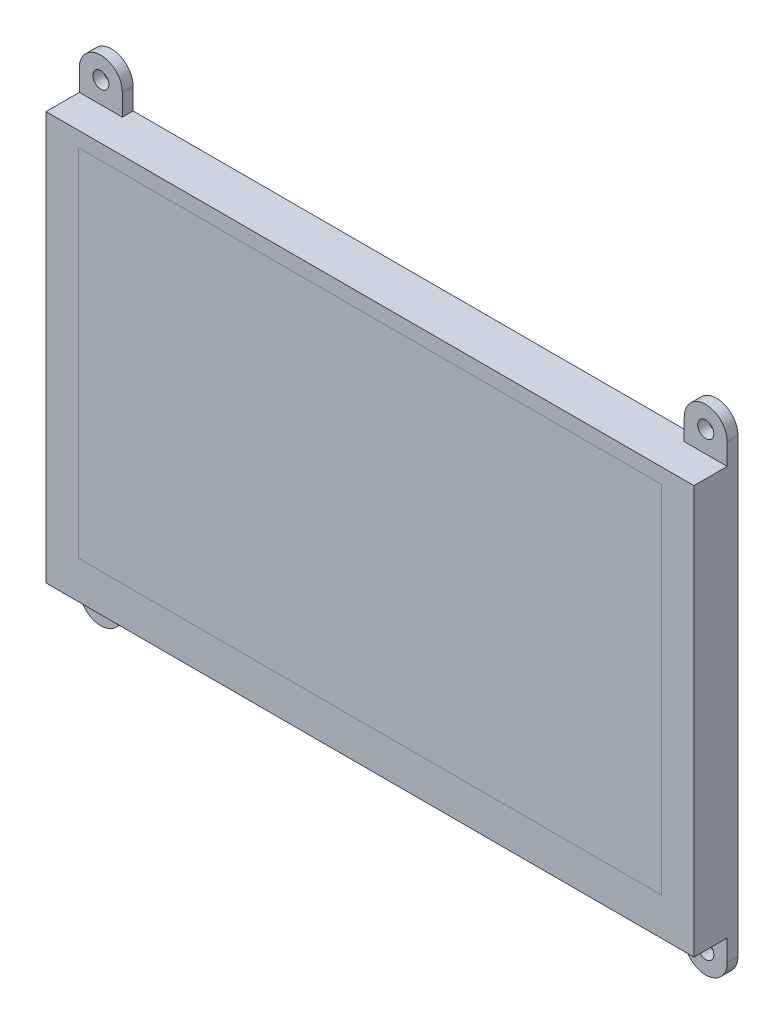
SolidWorks part; units mm, degrees
ref_plane "Front Plane" through (0, 0, 0) normal (0, 0, 1) x (1, 0, 0)
ref_plane "Top Plane" through (0, 0, 0) normal (0, 1, 0) x (1, 0, 0)
ref_plane "Right Plane" through (0, 0, 0) normal (1, 0, 0) x (0, 0, -1)
sketch "Sketch1" plane through (0, 0, 0) normal (0, 0, 1) x (1, 0, 0)
  line L0 (-60.3, 38) -> (-60.3, 42)
  line L1 (-60.3, -38) -> (60.3, -38)
  line L2 (-60.3, -38) -> (-60.3, 38)
  line L3 (-60.3, 38) -> (60.3, 38)
  line L4 (60.3, -38) -> (60.3, 38)
  line L5 (-60.3, -38) -> (60.3, 38) construction
  line L6 (-60.3, 38) -> (60.3, -38) construction
  line L7 (-52.3, 42) -> (-52.3, 38)
  line L8 (0, 0) -> (0, 68.3936) construction
  line L9 (0, 0) -> (-79.2473, 0) construction
  line L10 (52.3, 42) -> (52.3, 38)
  line L11 (60.3, 38) -> (60.3, 42)
  line L12 (60.3, -38) -> (60.3, -42)
  line L13 (52.3, -42) -> (52.3, -38)
  line L14 (-52.3, -42) -> (-52.3, -38)
  line L15 (-60.3, -38) -> (-60.3, -42)
  circle A0 centre (-56.3, 42) radius 4
  circle A2 centre (-56.3, 42) radius 1.5
  circle A3 centre (56.3, 42) radius 1.5
  circle A4 centre (56.3, 42) radius 4
  circle A5 centre (56.3, -42) radius 4
  circle A6 centre (56.3, -42) radius 1.5
  circle A7 centre (-56.3, -42) radius 1.5
  circle A8 centre (-56.3, -42) radius 4
  point P0 (0, 0)
  dimension "D3" = 3
  dimension "D4" = 8
  dimension "D1" = 76
  dimension "D2" = 120.6
extrude "Boss-Extrude1" add sketch "Sketch1" along normal blind 2 contours A0 A2 | A0 L0 L3 | A0 L3 L7 | L1 L4 L3 L2 | L11 A4 L3 | A4 A3 | L3 A4 L10 | L1 A8 L14 | L15 A8 L1 | A8 A7 | A5 L1 L13 | A5 A6 | A5 L12 L1
sketch "Sketch4" plane through (0, 0, 2) normal (0, 0, 1) x (1, 0, 0)
  line L0 (60.3, -42) -> (60.3, 42) construction
  line L1 (-60.3, -38) -> (60.3, -38)
  line L2 (-60.3, -38) -> (-60.3, 38)
  line L3 (-60.3, 38) -> (60.3, 38)
  line L4 (60.3, -38) -> (60.3, 38)
  line L5 (-60.3, -38) -> (60.3, 38) construction
  line L6 (-60.3, 38) -> (60.3, -38) construction
  line L7 (-52.3, 38) -> (52.3, 38) construction
  point P0 (0, 0)
  point P8 (0, 0)
extrude "Boss-Extrude3" add sketch "Sketch4" along normal blind 6.2
sketch "Sketch5" plane through (0, 0, 8.2) normal (0, 0, 1) x (1, 0, 0)
  line L0 (60.3, -38) -> (60.3, 38) construction
  line L1 (-54.3, 35.2) -> (54.3, 35.2)
  line L2 (-54.3, 35.2) -> (-54.3, -31)
  line L3 (-54.3, -31) -> (54.3, -31)
  line L4 (54.3, 35.2) -> (54.3, -31)
  line L5 (-54.3, 35.2) -> (54.3, -31) construction
  line L6 (-54.3, -31) -> (54.3, 35.2) construction
  line L7 (-60.3, 38) -> (-60.3, -38) construction
  line L8 (60.3, 38) -> (-60.3, 38) construction
  line L9 (-60.3, -38) -> (60.3, -38) construction
  point P0 (0, 2.1)
  dimension "D1" = 6
  dimension "D2" = 6
  dimension "D3" = 2.8
  dimension "D4" = 7
split line "Split Line1"
